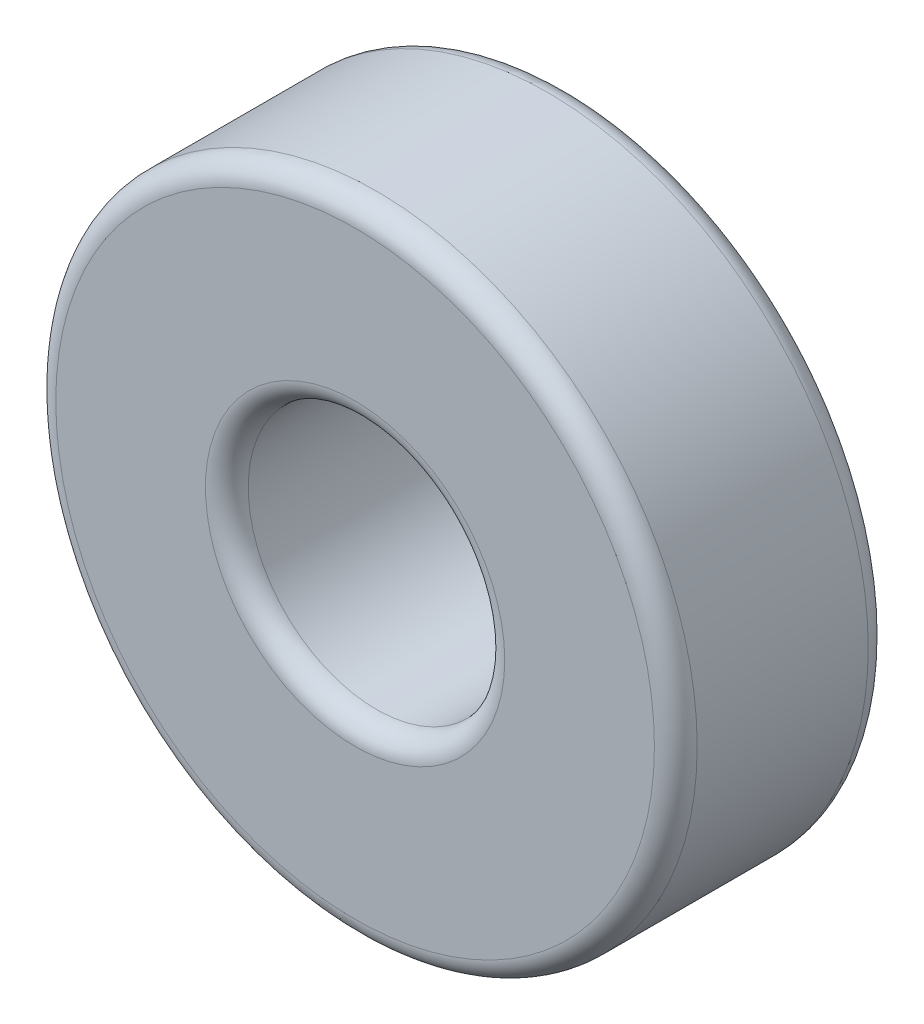
SolidWorks part; units mm, degrees
ref_plane "Front" through (0, 0, 0) normal (0, 0, 1) x (1, 0, 0)
ref_plane "Top" through (0, 0, 0) normal (0, 1, 0) x (1, 0, 0)
ref_plane "Right" through (0, 0, 0) normal (1, 0, 0) x (0, 0, -1)
sketch "Esquisse1" plane through (0, 0, 0) normal (0, 0, 1) x (1, 0, 0)
  circle A0 centre (0, 0) radius 3
  circle A1 centre (0, 0) radius 7.5
  dimension "D1" = 6
  dimension "D2" = 15
extrude "Boss.-Extru.1" add sketch "Esquisse1" along normal blind 5
fillet "Congé1" radius 0.5 4 edges at (3, 0, 0) (7.5, 0, 0) (3, 0, 5) (7.5, 0, 5)
